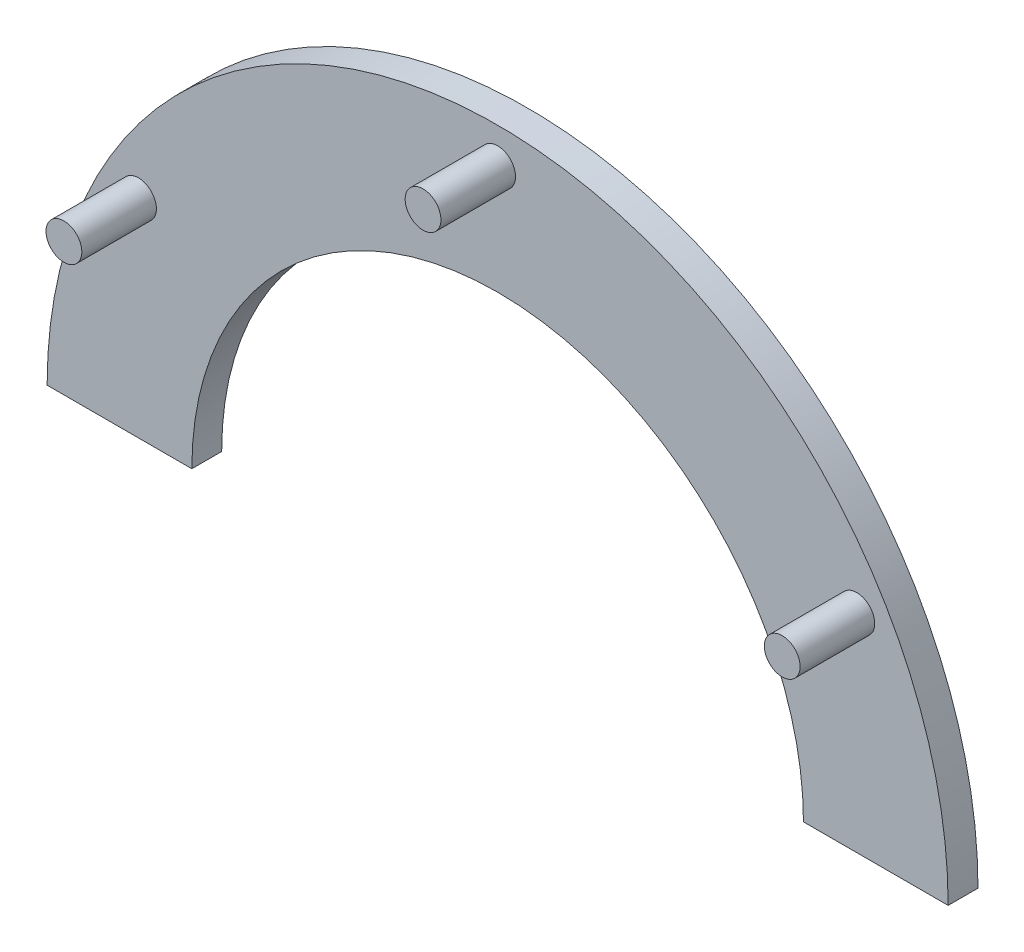
SolidWorks part; units mm, degrees
ref_plane "Front Plane" through (0, 0, 0) normal (0, 0, 1) x (1, 0, 0)
ref_plane "Top Plane" through (0, 0, 0) normal (0, 1, 0) x (1, 0, 0)
ref_plane "Right Plane" through (0, 0, 0) normal (1, 0, 0) x (0, 0, -1)
sketch "Sketch3" plane through (0, 0, 0) normal (0, 0, 1) x (1, 0, 0)
  line L0 (30.2, 0) -> (20.5, 0)
  line L1 (-20.5, 0) -> (-30.2, 0)
  arc A0 (20.5, 0) -> (-20.5, 0) centre (0, 0) ccw
  arc A1 (30.2, 0) -> (-30.2, 0) centre (0, 0) ccw
  dimension "D1" = 20.5
  dimension "D2" = 30.2
extrude "Boss-Extrude1" add sketch "Sketch3" along normal blind 2
sketch "Sketch4" plane through (0, 0, 0) normal (0, 0, -1) x (-1, 0, 0)
  line L0 (0, 0) -> (0, 27.8) construction
  line L1 (0, 0) -> (24.0755, 13.9) construction
  circle A0 centre (0, 27.8) radius 1.2
  arc A2 (20.5, 0) -> (-20.5, 0) centre (0, 0) ccw construction
  circle A3 centre (24.0755, 13.9) radius 1.2
  circle A7 centre (-24.0755, 13.9) radius 1.2
  circle A8 centre (-24.0755, -13.9) radius 1.2 [skipped]
  circle A9 centre (0, -27.8) radius 1.2 [skipped]
  circle A10 centre (24.0755, -13.9) radius 1.2 [skipped]
  point P2 (0, 0)
  dimension "D1" = 2.4
  dimension "D2" = 27.8
  dimension "D4" = 60
  dimension "D3" = 6
extrude "Boss-Extrude2" add sketch "Sketch4" against normal blind 7
